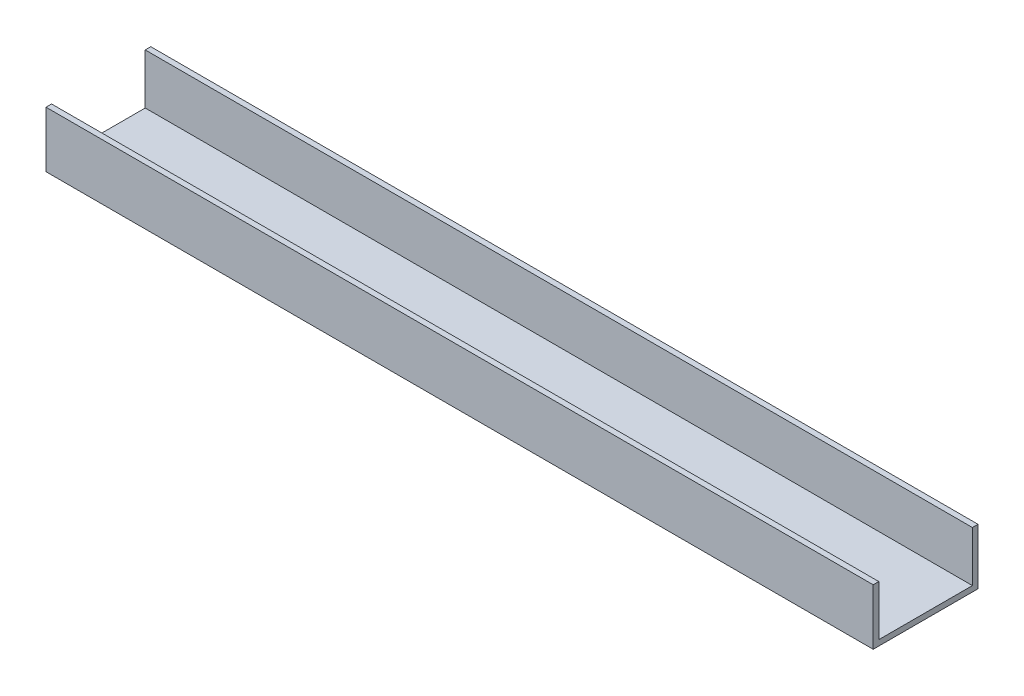
SolidWorks part; units mm, degrees
ref_plane "정면" through (0, 0, 0) normal (0, 0, 1) x (1, 0, 0)
ref_plane "윗면" through (0, 0, 0) normal (0, 1, 0) x (1, 0, 0)
ref_plane "우측면" through (0, 0, 0) normal (1, 0, 0) x (0, 0, -1)
sketch "스케치3" plane through (0, 0, 0) normal (0, 1, 0) x (1, 0, 0)
  line L1 (0, 0) -> (592, 0)
  line L2 (0, 0) -> (0, 75)
  line L3 (0, 75) -> (592, 75)
  line L4 (592, 0) -> (592, 75)
  dimension "D1" = 75
  dimension "D2" = 592
extrude "보스-돌출2" add sketch "스케치3" along normal blind 4
sketch "스케치4" plane through (0, 4, 0) normal (0, 1, 0) x (1, 0, 0)
  line L0 (592, 0) -> (592, 75) construction
  line L1 (0, 0) -> (592, 0)
  line L2 (0, 0) -> (0, 4)
  line L3 (0, 4) -> (592, 4)
  line L4 (592, 0) -> (592, 4)
  line L5 (0, 75) -> (0, 0) construction
  line L6 (592, 75) -> (0, 75)
  line L7 (592, 75) -> (592, 71)
  line L8 (592, 71) -> (0, 71)
  line L9 (0, 75) -> (0, 71)
  dimension "D1" = 4
  dimension "D2" = 4
extrude "보스-돌출3" add sketch "스케치4" along normal blind 36
ref_plane "평면1" through (0, 40, 0) normal (0, -1, 0) x (-1, 0, 0)
